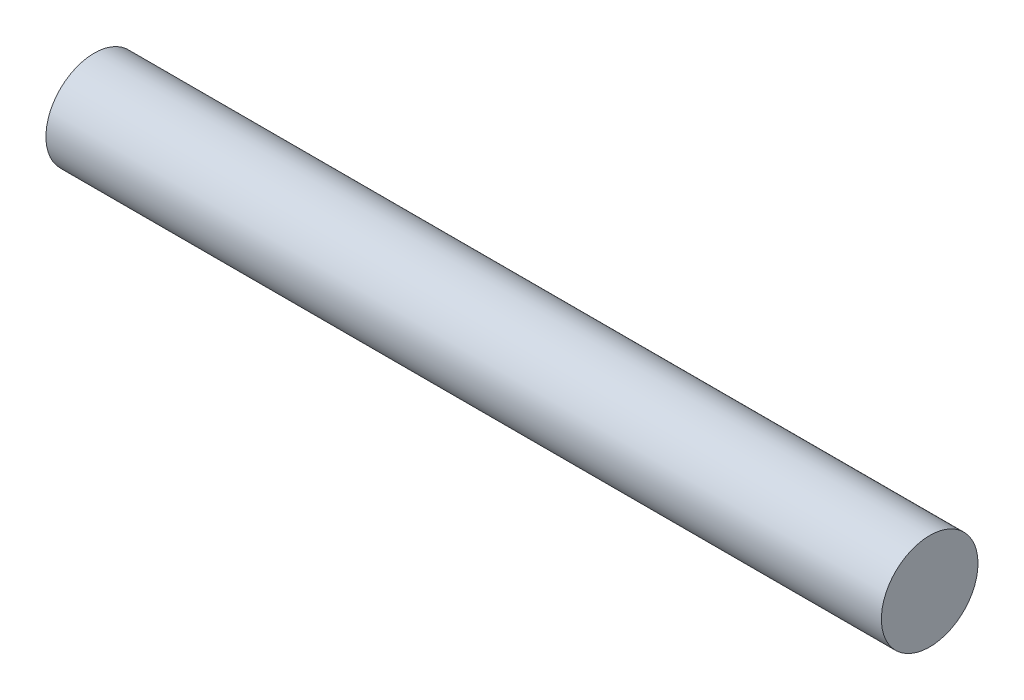
SolidWorks part; units mm, degrees
ref_plane "Front Plane" through (0, 0, 0) normal (0, 0, 1) x (1, 0, 0)
ref_plane "Top Plane" through (0, 0, 0) normal (0, 1, 0) x (1, 0, 0)
ref_plane "Right Plane" through (0, 0, 0) normal (1, 0, 0) x (0, 0, -1)
sketch "Sketch1" plane through (0, 0, 0) normal (1, 0, 0) x (0, 0, -1)
  circle A0 centre (0, 0) radius 0.925
  dimension "D1" = 1.85
extrude "Boss-Extrude1" add sketch "Sketch1" along normal blind 16 contours A0
